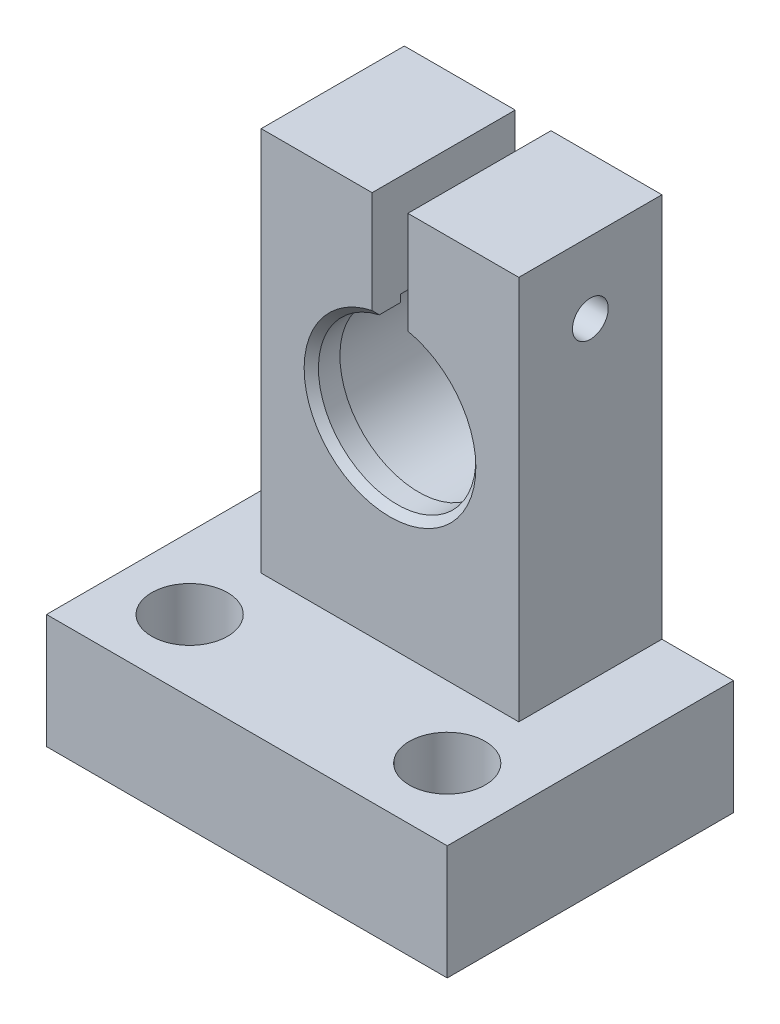
SolidWorks part; units mm, degrees
material "AISI 1045 Steel, cold drawn"
ref_plane "Front Plane" through (0, 0, 0) normal (0, 0, 1) x (1, 0, 0)
ref_plane "Top Plane" through (0, 0, 0) normal (0, 1, 0) x (1, 0, 0)
ref_plane "Right Plane" through (0, 0, 0) normal (1, 0, 0) x (0, 0, -1)
sketch "Sketch1" plane through (0, 0, 0) normal (0, 0, 1) x (1, 0, 0)
  line L1 (9, -21.9) -> (-9, -21.9)
  line L2 (9, -21.9) -> (9, 13)
  line L3 (9, 13) -> (-9, 13)
  line L4 (-9, -21.9) -> (-9, 13)
  line L5 (9, -21.9) -> (-9, 13) construction
  line L6 (9, 13) -> (-9, -21.9) construction
  circle A0 centre (0, 0) radius 6
  point P3 (0, -4.45)
  dimension "D1" = 12
  dimension "D2" = 13
  dimension "D3" = 21.9
  dimension "D4" = 18
extrude "Boss-Extrude1" add sketch "Sketch1" along normal blind 10
sketch "Sketch2" plane through (0, 0, 10) normal (0, 0, -1) x (-1, 0, 0)
  circle A0 centre (0, 0) radius 6 construction
  circle A1 centre (0, 0) radius 6
  circle A2 centre (0, 0) radius 5.5
  dimension "D1" = 0.5
extrude "Boss-Extrude2" add sketch "Sketch2" along normal blind 2
sketch "Sketch3" plane through (0, 0, 10) normal (0, 0, 1) x (1, 0, 0)
  line L0 (9, 13) -> (-9, 13) construction
  line L1 (1.25, 5.3561) -> (-1.25, 5.3561)
  line L2 (1.25, 5.3561) -> (1.25, 13)
  line L3 (1.25, 13) -> (-1.25, 13)
  line L4 (-1.25, 5.3561) -> (-1.25, 13)
  line L5 (1.25, 5.3561) -> (-1.25, 13) construction
  line L6 (1.25, 13) -> (-1.25, 5.3561) construction
  circle A0 centre (0, 0) radius 5.5 construction
  point P0 (0, 9.178)
  dimension "D1" = 2.5
extrude "Cut-Extrude1" cut sketch "Sketch3" against normal through all
hole_wizard "CBORE for M3 SHCS1" positions "Sketch4" profile "Sketch5" counterbore size "M3" standard "ANSI Metric"
sketch "Sketch4" plane through (9, 0, 0) normal (1, 0, 0) x (0, 0, -1)
  line L0 (0, -21.9) -> (0, 13) construction
  line L1 (-10, 13) -> (0, 13) construction
  point P0 (-5, 8)
  dimension "D1" = 5
  dimension "D2" = 5
sketch "Sketch5" plane through (9, 8, 5) normal (0, 1, 0) x (0, 0, -1)
  line L0 (0, 0) -> (0, 7.75)
  line L1 (0, 7.75) -> (1.6, 7.75)
  line L3 (1.6, 7.75) -> (1.6, 3)
  line L4 (1.6, 3) -> (3.25, 3)
  line L5 (3.25, 3) -> (3.25, 0)
  line L7 (3.25, 0) -> (0, 0)
  line L11 (0, -6.35) -> (0, 107.95) construction
  dimension "Thru Hole Dia." = 3.2
  dimension "Thru Hole Depth" = 7.75
  dimension "C'Bore Dia." = 6.5
  dimension "C'Bore Depth" = 3
hole_wizard "Tap Drill for M3x0.5 Tap1" positions "Sketch6" profile "Sketch7" hole size "M3x0.5" standard "ANSI Metric" end condition up to next
sketch "Sketch6" plane through (-9, 0, 0) normal (-1, 0, 0) x (0, 0, 1)
  line L0 (10, 13) -> (10, -21.9) construction
  line L1 (10, 13) -> (0, 13) construction
  point P0 (5, 8)
  dimension "D1" = 5
  dimension "D2" = 5
sketch "Sketch7" plane through (-9, 8, 5) normal (0, 1, 0) x (0, 0, 1)
  line L0 (0, 0) -> (0, 7.75)
  line L1 (0, 7.75) -> (1.25, 7.75)
  line L2 (1.25, 7.75) -> (1.25, 0)
  line L5 (1.25, 0) -> (0, 0)
  line L11 (0, -6.35) -> (0, 107.95) construction
  dimension "Thru Hole Dia." = 2.5
  dimension "Thru Hole Depth" = 7.75
chamfer "Chamfer1" distance 0.5 angle 45 2 edges at (0, -5.5, 10) (0, -6, 0)
sketch "Sketch11" plane through (-9, 0, 0) normal (-1, 0, 0) x (0, 0, 1)
  line L0 (0, 13) -> (0, -21.9) construction
  line L1 (0, -21.9) -> (10, -21.9)
  line L2 (0, -21.9) -> (0, -13.9)
  line L3 (0, -13.9) -> (10, -13.9)
  line L4 (10, -21.9) -> (10, -13.9)
  line L5 (10, 13) -> (10, -21.9) construction
  dimension "D1" = 8
extrude "Boss-Extrude4" add sketch "Sketch11" along normal blind 5
mirror "Mirror1" about plane through (0, 0, 0) normal (1, 0, 0) of "Boss-Extrude4"
sketch "Sketch8" plane through (0, -21.9, 0) normal (0, -1, 0) x (1, 0, 0)
  line L0 (-14, 0) -> (-14, 10) construction
  line L1 (-14, 10) -> (14, 10)
  line L2 (-14, 10) -> (-14, 20)
  line L3 (-14, 20) -> (14, 20)
  line L4 (14, 10) -> (14, 20)
  dimension "D1" = 10
extrude "Boss-Extrude3" add sketch "Sketch8" against normal up to surface (8 mm away) up to face at (-11.5, -13.9, 5)
hole_wizard "M5 Clearance Hole1" positions "Sketch9" profile "Sketch10" hole size "M5" standard "ANSI Metric" end condition up to next
sketch "Sketch9" plane through (0, -13.9, 0) normal (0, 1, 0) x (1, 0, 0)
  line L0 (14, -20) -> (-14, -20) construction
  line L1 (-14, -20) -> (-14, 0) construction
  line L2 (0, -10) -> (0, -20) construction
  line L4 (-9, -10) -> (9, -10) construction
  point P0 (-9, -15)
  point P14 (9, -15)
  dimension "D1" = 5
  dimension "D2" = 5
sketch "Sketch10" plane through (-9, -13.9, 15) normal (1, 0, 0) x (0, 0, 1)
  line L0 (0, 0) -> (0, 8)
  line L1 (0, 8) -> (2.65, 8)
  line L2 (2.65, 8) -> (2.65, 0)
  line L5 (2.65, 0) -> (0, 0)
  line L11 (0, -6.35) -> (0, 107.95) construction
  dimension "Thru Hole Dia." = 5.3
  dimension "Thru Hole Depth" = 8
mirror "Mirror2" about plane through (14, 0, 0) normal (-1, 0, 0) of bodies 107
delete or keep bodies "Body-Delete/Keep 1" type delete bodies bodies 107
